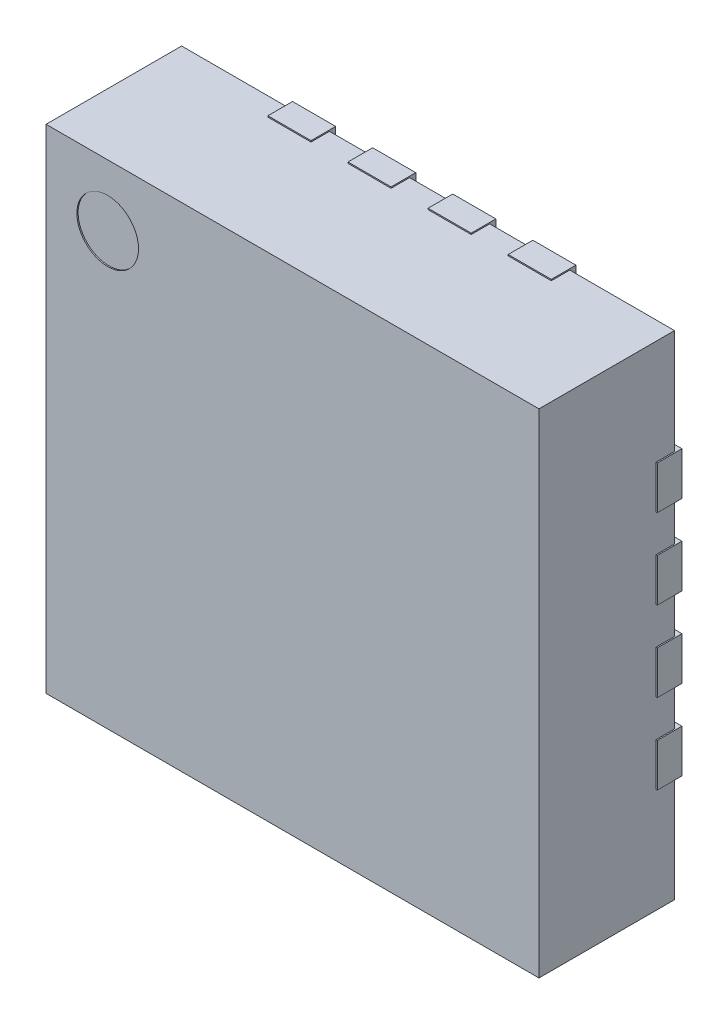
SolidWorks part; units mm, degrees
ref_plane "Plano frontal" through (0, 0, 0) normal (0, 0, 1) x (1, 0, 0)
ref_plane "Plano superior" through (0, 0, 0) normal (0, 1, 0) x (1, 0, 0)
ref_plane "Plano direito" through (0, 0, 0) normal (1, 0, 0) x (0, 0, -1)
ref_plane "Plano1" through (0, 0, 0.05) normal (0, 0, 1) x (1, 0, 0)
sketch "Esboço1" plane through (0, 0, 0.05) normal (0, 0, 1) x (1, 0, 0)
  line L1 (-2, 2) -> (2, 2)
  line L2 (-2, 2) -> (-2, -2)
  line L3 (-2, -2) -> (2, -2)
  line L4 (2, 2) -> (2, -2)
  line L5 (-2, 2) -> (2, -2) construction
  line L6 (-2, -2) -> (2, 2) construction
  point P0 (0, 0)
  dimension "D1" = 4
  dimension "D2" = 4
extrude "Ressalto-extrusão1" add sketch "Esboço1" along normal blind 1.1
sketch "Esboço2" plane through (0, 0, 0) normal (0, 0, 1) x (1, 0, 0)
  line L0 (0, 2) -> (0, -2) construction
  line L1 (-1.05, -1.05) -> (1.05, -1.05)
  line L2 (-1.05, -1.05) -> (-1.05, 0.75)
  line L3 (-0.75, 1.05) -> (1.05, 1.05)
  line L4 (1.05, -1.05) -> (1.05, 1.05)
  line L5 (-1.05, -1.05) -> (1.05, 1.05) construction
  line L6 (-1.05, 1.05) -> (1.05, -1.05) construction
  line L7 (2, 2) -> (-2, 2) construction
  line L8 (-2, -2) -> (2, -2) construction
  line L9 (-1.15, -1.635) -> (-0.8, -1.635) construction
  line L10 (-0.8, -2.01) -> (-1.15, -2.01)
  line L11 (-1.15, -2.01) -> (-1.15, -1.635)
  line L12 (-0.975, -2.0402) -> (-0.975, -1.635) construction
  line L13 (-0.8, -2.01) -> (-0.8, -1.635)
  line L14 (-0.5, -2.01) -> (-0.5, -1.635)
  line L15 (-0.15, -2.01) -> (-0.5, -2.01)
  line L16 (-0.15, -2.01) -> (-0.15, -1.635)
  line L17 (0.15, -2.01) -> (0.15, -1.635)
  line L18 (0.5, -2.01) -> (0.15, -2.01)
  line L19 (0.5, -2.01) -> (0.5, -1.635)
  line L20 (0.8, -2.01) -> (0.8, -1.635)
  line L21 (1.15, -2.01) -> (0.8, -2.01)
  line L22 (1.15, -2.01) -> (1.15, -1.635)
  line L23 (-2.01, 0.8) -> (-2.01, 1.15)
  line L24 (-2.01, 1.15) -> (-1.635, 1.15)
  line L25 (-2.01, 0.8) -> (-1.635, 0.8)
  line L26 (-2.01, 0.5) -> (-1.635, 0.5)
  line L27 (-2.01, 0.15) -> (-2.01, 0.5)
  line L28 (-2.01, 0.15) -> (-1.635, 0.15)
  line L29 (-2.01, -0.15) -> (-1.635, -0.15)
  line L30 (-2.01, -0.5) -> (-2.01, -0.15)
  line L31 (-2.01, -0.5) -> (-1.635, -0.5)
  line L32 (-2.01, -0.8) -> (-1.635, -0.8)
  line L33 (-2.01, -1.15) -> (-2.01, -0.8)
  line L34 (-2.01, -1.15) -> (-1.635, -1.15)
  line L35 (0.8, 2.01) -> (1.15, 2.01)
  line L36 (1.15, 2.01) -> (1.15, 1.635)
  line L37 (0.8, 2.01) -> (0.8, 1.635)
  line L38 (0.5, 2.01) -> (0.5, 1.635)
  line L39 (0.15, 2.01) -> (0.5, 2.01)
  line L40 (0.15, 2.01) -> (0.15, 1.635)
  line L41 (-0.15, 2.01) -> (-0.15, 1.635)
  line L42 (-0.5, 2.01) -> (-0.15, 2.01)
  line L43 (-0.5, 2.01) -> (-0.5, 1.635)
  line L44 (-0.8, 2.01) -> (-0.8, 1.635)
  line L45 (-1.15, 2.01) -> (-0.8, 2.01)
  line L46 (-1.15, 2.01) -> (-1.15, 1.635)
  line L47 (2.01, -0.8) -> (2.01, -1.15)
  line L48 (2.01, -1.15) -> (1.635, -1.15)
  line L49 (2.01, -0.8) -> (1.635, -0.8)
  line L50 (2.01, -0.5) -> (1.635, -0.5)
  line L51 (2.01, -0.15) -> (2.01, -0.5)
  line L52 (2.01, -0.15) -> (1.635, -0.15)
  line L53 (2.01, 0.15) -> (1.635, 0.15)
  line L54 (2.01, 0.5) -> (2.01, 0.15)
  line L55 (2.01, 0.5) -> (1.635, 0.5)
  line L56 (2.01, 0.8) -> (1.635, 0.8)
  line L57 (2.01, 1.15) -> (2.01, 0.8)
  line L58 (2.01, 1.15) -> (1.635, 1.15)
  line L59 (-1.05, 0.75) -> (-0.75, 1.05)
  arc A0 (-0.8, -1.635) -> (-1.15, -1.635) centre (-0.975, -1.635) ccw
  arc A1 (-0.15, -1.635) -> (-0.5, -1.635) centre (-0.325, -1.635) ccw
  arc A2 (0.5, -1.635) -> (0.15, -1.635) centre (0.325, -1.635) ccw
  arc A3 (1.15, -1.635) -> (0.8, -1.635) centre (0.975, -1.635) ccw
  arc A4 (-1.635, 0.8) -> (-1.635, 1.15) centre (-1.635, 0.975) ccw
  arc A5 (-1.635, 0.15) -> (-1.635, 0.5) centre (-1.635, 0.325) ccw
  arc A6 (-1.635, -0.5) -> (-1.635, -0.15) centre (-1.635, -0.325) ccw
  arc A7 (-1.635, -1.15) -> (-1.635, -0.8) centre (-1.635, -0.975) ccw
  arc A8 (0.8, 1.635) -> (1.15, 1.635) centre (0.975, 1.635) ccw
  arc A9 (0.15, 1.635) -> (0.5, 1.635) centre (0.325, 1.635) ccw
  arc A10 (-0.5, 1.635) -> (-0.15, 1.635) centre (-0.325, 1.635) ccw
  arc A11 (-1.15, 1.635) -> (-0.8, 1.635) centre (-0.975, 1.635) ccw
  arc A12 (1.635, -0.8) -> (1.635, -1.15) centre (1.635, -0.975) ccw
  arc A13 (1.635, -0.15) -> (1.635, -0.5) centre (1.635, -0.325) ccw
  arc A14 (1.635, 0.5) -> (1.635, 0.15) centre (1.635, 0.325) ccw
  arc A15 (1.635, 1.15) -> (1.635, 0.8) centre (1.635, 0.975) ccw
  point P0 (0, 0)
  point P35 (1.3547, 1.5881)
  point P96 (0, 0)
  point P97 (0, 0)
  point P98 (-1.6475, -0.9625)
  dimension "D2" = 2.1
  dimension "D3" = 0.35
  dimension "D4" = 0.375
  dimension "D5" = 0.975
  dimension "D6" = 0.01
  dimension "D8" = 0.65
  dimension "D11" = 2.1
  dimension "D7" = 4
  dimension "D9" = 4
extrude "Ressalto-extrusão2" add sketch "Esboço2" along normal blind 0.2
sketch "Esboço3" plane through (0, 0, 1.15) normal (0, 0, 1) x (1, 0, 0)
  line L0 (2, 2) -> (-2, 2) construction
  line L2 (-2, 2) -> (-2, -2) construction
  circle A0 centre (-1.5, 1.5) radius 0.25
  dimension "D3" = 0.5
  dimension "D1" = 0.5
  dimension "D2" = 0.5
extrude "Corte-extrusão1" cut sketch "Esboço3" against normal blind 0.01
